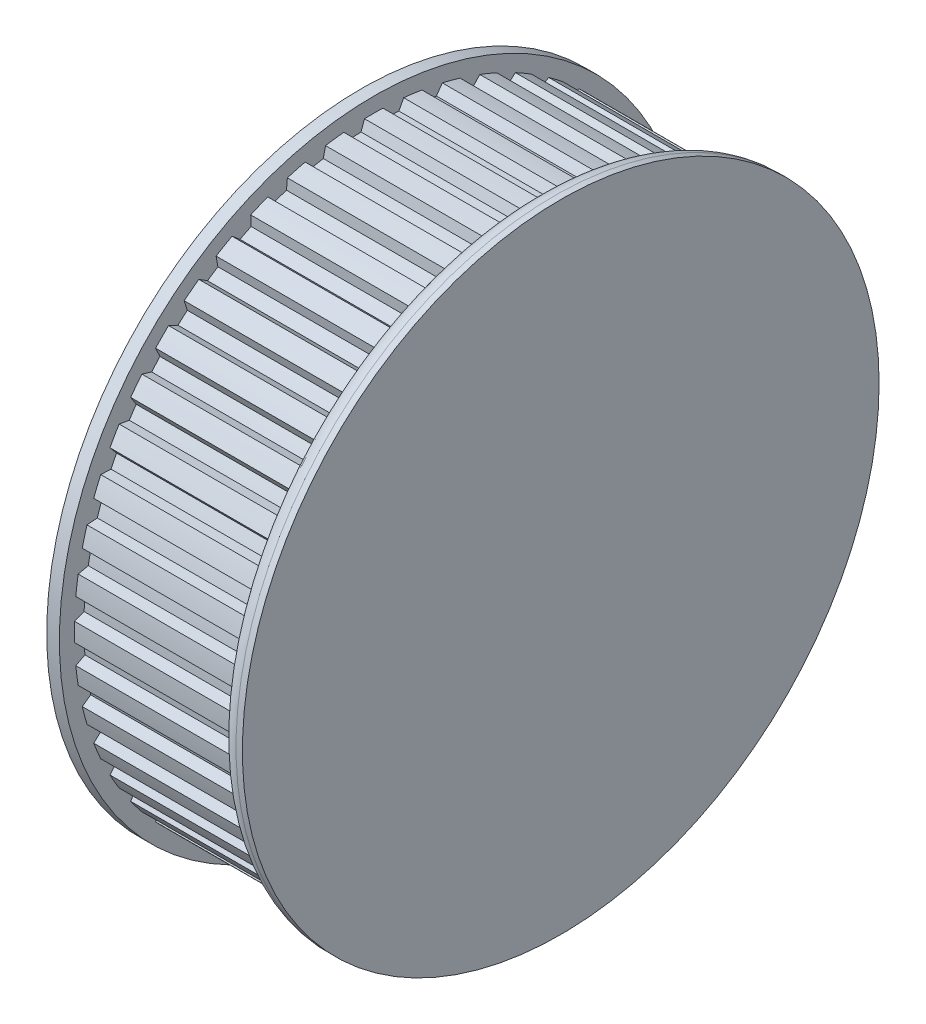
SolidWorks part; units mm, degrees
ref_plane "Front Plane" through (0, 0, 0) normal (0, 0, 1) x (1, 0, 0)
ref_plane "Top Plane" through (0, 0, 0) normal (0, 1, 0) x (1, 0, 0)
ref_plane "Right Plane" through (0, 0, 0) normal (1, 0, 0) x (0, 0, -1)
ref_plane "Plane1" through (0, 0, 0) normal (0, 0, -1) x (-1, 0, 0)
sketch "Sketch1" plane through (0, 0, 0) normal (0, 0, -1) x (-1, 0, 0)
  line L0 (-20.5, 37.625) -> (-20.5, 0)
  line L1 (-20.5, 0) -> (0, 0)
  line L2 (0, 0) -> (0, 37.625)
  line L3 (0, 37.625) -> (-20.5, 37.625)
  line L4 (-20.5, 0) -> (0, 0) construction
revolve "Revolve1" add sketch "Sketch1" angle 360 about L4
sketch "Sketch2" plane through (0, 0, 0) normal (-1, 0, 0) x (0, 0, 1)
  line L0 (-37.6072, 1.1569) -> (-36.3898, 1.6)
  line L1 (-36.2874, 3.1635) -> (-37.4365, 3.7617)
  arc A0 (-37.4365, 3.7617) -> (-37.6072, 1.1569) centre (0, 0) ccw
  arc A1 (-36.3898, 1.6) -> (-36.2874, 3.1635) centre (0, 0) cw
extrude "Cut-Extrude1" cut sketch "Sketch2" against normal through all
sketch "Sketch3" plane through (0, 0, 0) normal (-1, 0, 0) x (0, 0, 1)
  line L0 (-37.1345, 6.0557) -> (-35.8697, 6.3361)
  line L1 (-35.564, 7.8729) -> (-36.6252, 8.616)
  arc A0 (-36.6252, 8.616) -> (-37.1345, 6.0557) centre (0, 0) ccw
  arc A1 (-35.8697, 6.3361) -> (-35.564, 7.8729) centre (0, 0) cw
extrude "Cut-Extrude2" cut sketch "Sketch3" against normal through all
sketch "Sketch4" plane through (0, 0, 0) normal (-1, 0, 0) x (0, 0, 1)
  line L0 (-36.0263, 10.851) -> (-34.7358, 10.9639)
  line L1 (-34.2321, 12.4476) -> (-35.1873, 13.3228)
  arc A0 (-35.1873, 13.3228) -> (-36.0263, 10.851) centre (0, 0) ccw
  arc A1 (-34.7358, 10.9639) -> (-34.2321, 12.4476) centre (0, 0) cw
extrude "Cut-Extrude3" cut sketch "Sketch4" against normal through all
sketch "Sketch5" plane through (0, 0, 0) normal (-1, 0, 0) x (0, 0, 1)
  line L0 (-34.3018, 15.4605) -> (-33.0075, 15.404)
  line L1 (-32.3145, 16.8093) -> (-33.1473, 17.8017)
  arc A0 (-33.1473, 17.8017) -> (-34.3018, 15.4605) centre (0, 0) ccw
  arc A1 (-33.0075, 15.404) -> (-32.3145, 16.8093) centre (0, 0) cw
extrude "Cut-Extrude4" cut sketch "Sketch5" against normal through all
sketch "Sketch6" plane through (0, 0, 0) normal (-1, 0, 0) x (0, 0, 1)
  line L0 (-31.9903, 19.8055) -> (-30.7145, 19.5806)
  line L1 (-29.844, 20.8834) -> (-30.5401, 21.976)
  arc A0 (-30.5401, 21.976) -> (-31.9903, 19.8055) centre (0, 0) ccw
  arc A1 (-30.7145, 19.5806) -> (-29.844, 20.8834) centre (0, 0) cw
extrude "Cut-Extrude5" cut sketch "Sketch6" against normal through all
sketch "Sketch7" plane through (0, 0, 0) normal (-1, 0, 0) x (0, 0, 1)
  line L0 (-29.1315, 23.8117) -> (-27.896, 23.4221)
  line L1 (-26.8629, 24.6001) -> (-27.4104, 25.7743)
  arc A0 (-27.4104, 25.7743) -> (-29.1315, 23.8117) centre (0, 0) ccw
  arc A1 (-27.896, 23.4221) -> (-26.8629, 24.6001) centre (0, 0) cw
extrude "Cut-Extrude6" cut sketch "Sketch7" against normal through all
sketch "Sketch8" plane through (0, 0, 0) normal (-1, 0, 0) x (0, 0, 1)
  line L0 (-25.7743, 27.4104) -> (-24.6001, 26.8629)
  line L1 (-23.4221, 27.896) -> (-23.8117, 29.1315)
  arc A0 (-23.8117, 29.1315) -> (-25.7743, 27.4104) centre (0, 0) ccw
  arc A1 (-24.6001, 26.8629) -> (-23.4221, 27.896) centre (0, 0) cw
extrude "Cut-Extrude7" cut sketch "Sketch8" against normal through all
sketch "Sketch9" plane through (0, 0, 0) normal (-1, 0, 0) x (0, 0, 1)
  line L0 (-21.976, 30.5401) -> (-20.8834, 29.844)
  line L1 (-19.5806, 30.7145) -> (-19.8055, 31.9903)
  arc A0 (-19.8055, 31.9903) -> (-21.976, 30.5401) centre (0, 0) ccw
  arc A1 (-20.8834, 29.844) -> (-19.5806, 30.7145) centre (0, 0) cw
extrude "Cut-Extrude8" cut sketch "Sketch9" against normal through all
sketch "Sketch10" plane through (0, 0, 0) normal (-1, 0, 0) x (0, 0, 1)
  line L0 (-17.8017, 33.1473) -> (-16.8093, 32.3145)
  line L1 (-15.404, 33.0075) -> (-15.4605, 34.3018)
  arc A0 (-15.4605, 34.3018) -> (-17.8017, 33.1473) centre (0, 0) ccw
  arc A1 (-16.8093, 32.3145) -> (-15.404, 33.0075) centre (0, 0) cw
extrude "Cut-Extrude9" cut sketch "Sketch10" against normal through all
sketch "Sketch11" plane through (0, 0, 0) normal (-1, 0, 0) x (0, 0, 1)
  line L0 (-13.3228, 35.1873) -> (-12.4476, 34.2321)
  line L1 (-10.9639, 34.7358) -> (-10.851, 36.0263)
  arc A0 (-10.851, 36.0263) -> (-13.3228, 35.1873) centre (0, 0) ccw
  arc A1 (-12.4476, 34.2321) -> (-10.9639, 34.7358) centre (0, 0) cw
extrude "Cut-Extrude10" cut sketch "Sketch11" against normal through all
sketch "Sketch12" plane through (0, 0, 0) normal (-1, 0, 0) x (0, 0, 1)
  line L0 (-8.616, 36.6252) -> (-7.8729, 35.564)
  line L1 (-6.3361, 35.8697) -> (-6.0557, 37.1345)
  arc A0 (-6.0557, 37.1345) -> (-8.616, 36.6252) centre (0, 0) ccw
  arc A1 (-7.8729, 35.564) -> (-6.3361, 35.8697) centre (0, 0) cw
extrude "Cut-Extrude11" cut sketch "Sketch12" against normal through all
sketch "Sketch13" plane through (0, 0, 0) normal (-1, 0, 0) x (0, 0, 1)
  line L0 (-3.7617, 37.4365) -> (-3.1635, 36.2874)
  line L1 (-1.6, 36.3898) -> (-1.1569, 37.6072)
  arc A0 (-1.1569, 37.6072) -> (-3.7617, 37.4365) centre (0, 0) ccw
  arc A1 (-3.1635, 36.2874) -> (-1.6, 36.3898) centre (0, 0) cw
extrude "Cut-Extrude12" cut sketch "Sketch13" against normal through all
sketch "Sketch14" plane through (0, 0, 0) normal (-1, 0, 0) x (0, 0, 1)
  line L0 (1.1569, 37.6072) -> (1.6, 36.3898)
  line L1 (3.1635, 36.2874) -> (3.7617, 37.4365)
  arc A0 (3.7617, 37.4365) -> (1.1569, 37.6072) centre (0, 0) ccw
  arc A1 (1.6, 36.3898) -> (3.1635, 36.2874) centre (0, 0) cw
extrude "Cut-Extrude13" cut sketch "Sketch14" against normal through all
sketch "Sketch15" plane through (0, 0, 0) normal (-1, 0, 0) x (0, 0, 1)
  line L0 (6.0557, 37.1345) -> (6.3361, 35.8697)
  line L1 (7.8729, 35.564) -> (8.616, 36.6252)
  arc A0 (8.616, 36.6252) -> (6.0557, 37.1345) centre (0, 0) ccw
  arc A1 (6.3361, 35.8697) -> (7.8729, 35.564) centre (0, 0) cw
extrude "Cut-Extrude14" cut sketch "Sketch15" against normal through all
sketch "Sketch16" plane through (0, 0, 0) normal (-1, 0, 0) x (0, 0, 1)
  line L0 (10.851, 36.0263) -> (10.9639, 34.7358)
  line L1 (12.4476, 34.2321) -> (13.3228, 35.1873)
  arc A0 (13.3228, 35.1873) -> (10.851, 36.0263) centre (0, 0) ccw
  arc A1 (10.9639, 34.7358) -> (12.4476, 34.2321) centre (0, 0) cw
extrude "Cut-Extrude15" cut sketch "Sketch16" against normal through all
sketch "Sketch17" plane through (0, 0, 0) normal (-1, 0, 0) x (0, 0, 1)
  line L0 (15.4605, 34.3018) -> (15.404, 33.0075)
  line L1 (16.8093, 32.3145) -> (17.8017, 33.1473)
  arc A0 (17.8017, 33.1473) -> (15.4605, 34.3018) centre (0, 0) ccw
  arc A1 (15.404, 33.0075) -> (16.8093, 32.3145) centre (0, 0) cw
extrude "Cut-Extrude16" cut sketch "Sketch17" against normal through all
sketch "Sketch18" plane through (0, 0, 0) normal (-1, 0, 0) x (0, 0, 1)
  line L0 (19.8055, 31.9903) -> (19.5806, 30.7145)
  line L1 (20.8834, 29.844) -> (21.976, 30.5401)
  arc A0 (21.976, 30.5401) -> (19.8055, 31.9903) centre (0, 0) ccw
  arc A1 (19.5806, 30.7145) -> (20.8834, 29.844) centre (0, 0) cw
extrude "Cut-Extrude17" cut sketch "Sketch18" against normal through all
sketch "Sketch19" plane through (0, 0, 0) normal (-1, 0, 0) x (0, 0, 1)
  line L0 (23.8117, 29.1315) -> (23.4221, 27.896)
  line L1 (24.6001, 26.8629) -> (25.7743, 27.4104)
  arc A0 (25.7743, 27.4104) -> (23.8117, 29.1315) centre (0, 0) ccw
  arc A1 (23.4221, 27.896) -> (24.6001, 26.8629) centre (0, 0) cw
extrude "Cut-Extrude18" cut sketch "Sketch19" against normal through all
sketch "Sketch20" plane through (0, 0, 0) normal (-1, 0, 0) x (0, 0, 1)
  line L0 (27.4104, 25.7743) -> (26.8629, 24.6001)
  line L1 (27.896, 23.4221) -> (29.1315, 23.8117)
  arc A0 (29.1315, 23.8117) -> (27.4104, 25.7743) centre (0, 0) ccw
  arc A1 (26.8629, 24.6001) -> (27.896, 23.4221) centre (0, 0) cw
extrude "Cut-Extrude19" cut sketch "Sketch20" against normal through all
sketch "Sketch21" plane through (0, 0, 0) normal (-1, 0, 0) x (0, 0, 1)
  line L0 (30.5401, 21.976) -> (29.844, 20.8834)
  line L1 (30.7145, 19.5806) -> (31.9903, 19.8055)
  arc A0 (31.9903, 19.8055) -> (30.5401, 21.976) centre (0, 0) ccw
  arc A1 (29.844, 20.8834) -> (30.7145, 19.5806) centre (0, 0) cw
extrude "Cut-Extrude20" cut sketch "Sketch21" against normal through all
sketch "Sketch22" plane through (0, 0, 0) normal (-1, 0, 0) x (0, 0, 1)
  line L0 (33.1473, 17.8017) -> (32.3145, 16.8093)
  line L1 (33.0075, 15.404) -> (34.3018, 15.4605)
  arc A0 (34.3018, 15.4605) -> (33.1473, 17.8017) centre (0, 0) ccw
  arc A1 (32.3145, 16.8093) -> (33.0075, 15.404) centre (0, 0) cw
extrude "Cut-Extrude21" cut sketch "Sketch22" against normal through all
sketch "Sketch23" plane through (0, 0, 0) normal (-1, 0, 0) x (0, 0, 1)
  line L0 (35.1873, 13.3228) -> (34.2321, 12.4476)
  line L1 (34.7358, 10.9639) -> (36.0263, 10.851)
  arc A0 (36.0263, 10.851) -> (35.1873, 13.3228) centre (0, 0) ccw
  arc A1 (34.2321, 12.4476) -> (34.7358, 10.9639) centre (0, 0) cw
extrude "Cut-Extrude22" cut sketch "Sketch23" against normal through all
sketch "Sketch24" plane through (0, 0, 0) normal (-1, 0, 0) x (0, 0, 1)
  line L0 (36.6252, 8.616) -> (35.564, 7.8729)
  line L1 (35.8697, 6.3361) -> (37.1345, 6.0557)
  arc A0 (37.1345, 6.0557) -> (36.6252, 8.616) centre (0, 0) ccw
  arc A1 (35.564, 7.8729) -> (35.8697, 6.3361) centre (0, 0) cw
extrude "Cut-Extrude23" cut sketch "Sketch24" against normal through all
sketch "Sketch25" plane through (0, 0, 0) normal (-1, 0, 0) x (0, 0, 1)
  line L0 (37.4365, 3.7617) -> (36.2874, 3.1635)
  line L1 (36.3898, 1.6) -> (37.6072, 1.1569)
  arc A0 (37.6072, 1.1569) -> (37.4365, 3.7617) centre (0, 0) ccw
  arc A1 (36.2874, 3.1635) -> (36.3898, 1.6) centre (0, 0) cw
extrude "Cut-Extrude24" cut sketch "Sketch25" against normal through all
sketch "Sketch26" plane through (0, 0, 0) normal (-1, 0, 0) x (0, 0, 1)
  line L0 (37.6072, -1.1569) -> (36.3898, -1.6)
  line L1 (36.2874, -3.1635) -> (37.4365, -3.7617)
  arc A0 (37.4365, -3.7617) -> (37.6072, -1.1569) centre (0, 0) ccw
  arc A1 (36.3898, -1.6) -> (36.2874, -3.1635) centre (0, 0) cw
extrude "Cut-Extrude25" cut sketch "Sketch26" against normal through all
sketch "Sketch27" plane through (0, 0, 0) normal (-1, 0, 0) x (0, 0, 1)
  line L0 (37.1345, -6.0557) -> (35.8697, -6.3361)
  line L1 (35.564, -7.8729) -> (36.6252, -8.616)
  arc A0 (36.6252, -8.616) -> (37.1345, -6.0557) centre (0, 0) ccw
  arc A1 (35.8697, -6.3361) -> (35.564, -7.8729) centre (0, 0) cw
extrude "Cut-Extrude26" cut sketch "Sketch27" against normal through all
sketch "Sketch28" plane through (0, 0, 0) normal (-1, 0, 0) x (0, 0, 1)
  line L0 (36.0263, -10.851) -> (34.7358, -10.9639)
  line L1 (34.2321, -12.4476) -> (35.1873, -13.3228)
  arc A0 (35.1873, -13.3228) -> (36.0263, -10.851) centre (0, 0) ccw
  arc A1 (34.7358, -10.9639) -> (34.2321, -12.4476) centre (0, 0) cw
extrude "Cut-Extrude27" cut sketch "Sketch28" against normal through all
sketch "Sketch29" plane through (0, 0, 0) normal (-1, 0, 0) x (0, 0, 1)
  line L0 (34.3018, -15.4605) -> (33.0075, -15.404)
  line L1 (32.3145, -16.8093) -> (33.1473, -17.8017)
  arc A0 (33.1473, -17.8017) -> (34.3018, -15.4605) centre (0, 0) ccw
  arc A1 (33.0075, -15.404) -> (32.3145, -16.8093) centre (0, 0) cw
extrude "Cut-Extrude28" cut sketch "Sketch29" against normal through all
sketch "Sketch30" plane through (0, 0, 0) normal (-1, 0, 0) x (0, 0, 1)
  line L0 (31.9903, -19.8055) -> (30.7145, -19.5806)
  line L1 (29.844, -20.8834) -> (30.5401, -21.976)
  arc A0 (30.5401, -21.976) -> (31.9903, -19.8055) centre (0, 0) ccw
  arc A1 (30.7145, -19.5806) -> (29.844, -20.8834) centre (0, 0) cw
extrude "Cut-Extrude29" cut sketch "Sketch30" against normal through all
sketch "Sketch31" plane through (0, 0, 0) normal (-1, 0, 0) x (0, 0, 1)
  line L0 (29.1315, -23.8117) -> (27.896, -23.4221)
  line L1 (26.8629, -24.6001) -> (27.4104, -25.7743)
  arc A0 (27.4104, -25.7743) -> (29.1315, -23.8117) centre (0, 0) ccw
  arc A1 (27.896, -23.4221) -> (26.8629, -24.6001) centre (0, 0) cw
extrude "Cut-Extrude30" cut sketch "Sketch31" against normal through all
sketch "Sketch32" plane through (0, 0, 0) normal (-1, 0, 0) x (0, 0, 1)
  line L0 (25.7743, -27.4104) -> (24.6001, -26.8629)
  line L1 (23.4221, -27.896) -> (23.8117, -29.1315)
  arc A0 (23.8117, -29.1315) -> (25.7743, -27.4104) centre (0, 0) ccw
  arc A1 (24.6001, -26.8629) -> (23.4221, -27.896) centre (0, 0) cw
extrude "Cut-Extrude31" cut sketch "Sketch32" against normal through all
sketch "Sketch33" plane through (0, 0, 0) normal (-1, 0, 0) x (0, 0, 1)
  line L0 (21.976, -30.5401) -> (20.8834, -29.844)
  line L1 (19.5806, -30.7145) -> (19.8055, -31.9903)
  arc A0 (19.8055, -31.9903) -> (21.976, -30.5401) centre (0, 0) ccw
  arc A1 (20.8834, -29.844) -> (19.5806, -30.7145) centre (0, 0) cw
extrude "Cut-Extrude32" cut sketch "Sketch33" against normal through all
sketch "Sketch34" plane through (0, 0, 0) normal (-1, 0, 0) x (0, 0, 1)
  line L0 (17.8017, -33.1473) -> (16.8093, -32.3145)
  line L1 (15.404, -33.0075) -> (15.4605, -34.3018)
  arc A0 (15.4605, -34.3018) -> (17.8017, -33.1473) centre (0, 0) ccw
  arc A1 (16.8093, -32.3145) -> (15.404, -33.0075) centre (0, 0) cw
extrude "Cut-Extrude33" cut sketch "Sketch34" against normal through all
sketch "Sketch35" plane through (0, 0, 0) normal (-1, 0, 0) x (0, 0, 1)
  line L0 (13.3228, -35.1873) -> (12.4476, -34.2321)
  line L1 (10.9639, -34.7358) -> (10.851, -36.0263)
  arc A0 (10.851, -36.0263) -> (13.3228, -35.1873) centre (0, 0) ccw
  arc A1 (12.4476, -34.2321) -> (10.9639, -34.7358) centre (0, 0) cw
extrude "Cut-Extrude34" cut sketch "Sketch35" against normal through all
sketch "Sketch36" plane through (0, 0, 0) normal (-1, 0, 0) x (0, 0, 1)
  line L0 (8.616, -36.6252) -> (7.8729, -35.564)
  line L1 (6.3361, -35.8697) -> (6.0557, -37.1345)
  arc A0 (6.0557, -37.1345) -> (8.616, -36.6252) centre (0, 0) ccw
  arc A1 (7.8729, -35.564) -> (6.3361, -35.8697) centre (0, 0) cw
extrude "Cut-Extrude35" cut sketch "Sketch36" against normal through all
sketch "Sketch37" plane through (0, 0, 0) normal (-1, 0, 0) x (0, 0, 1)
  line L0 (3.7617, -37.4365) -> (3.1635, -36.2874)
  line L1 (1.6, -36.3898) -> (1.1569, -37.6072)
  arc A0 (1.1569, -37.6072) -> (3.7617, -37.4365) centre (0, 0) ccw
  arc A1 (3.1635, -36.2874) -> (1.6, -36.3898) centre (0, 0) cw
extrude "Cut-Extrude36" cut sketch "Sketch37" against normal through all
sketch "Sketch38" plane through (0, 0, 0) normal (-1, 0, 0) x (0, 0, 1)
  line L0 (-1.1569, -37.6072) -> (-1.6, -36.3898)
  line L1 (-3.1635, -36.2874) -> (-3.7617, -37.4365)
  arc A0 (-3.7617, -37.4365) -> (-1.1569, -37.6072) centre (0, 0) ccw
  arc A1 (-1.6, -36.3898) -> (-3.1635, -36.2874) centre (0, 0) cw
extrude "Cut-Extrude37" cut sketch "Sketch38" against normal through all
sketch "Sketch39" plane through (0, 0, 0) normal (-1, 0, 0) x (0, 0, 1)
  line L0 (-6.0557, -37.1345) -> (-6.3361, -35.8697)
  line L1 (-7.8729, -35.564) -> (-8.616, -36.6252)
  arc A0 (-8.616, -36.6252) -> (-6.0557, -37.1345) centre (0, 0) ccw
  arc A1 (-6.3361, -35.8697) -> (-7.8729, -35.564) centre (0, 0) cw
extrude "Cut-Extrude38" cut sketch "Sketch39" against normal through all
sketch "Sketch40" plane through (0, 0, 0) normal (-1, 0, 0) x (0, 0, 1)
  line L0 (-10.851, -36.0263) -> (-10.9639, -34.7358)
  line L1 (-12.4476, -34.2321) -> (-13.3228, -35.1873)
  arc A0 (-13.3228, -35.1873) -> (-10.851, -36.0263) centre (0, 0) ccw
  arc A1 (-10.9639, -34.7358) -> (-12.4476, -34.2321) centre (0, 0) cw
extrude "Cut-Extrude39" cut sketch "Sketch40" against normal through all
sketch "Sketch41" plane through (0, 0, 0) normal (-1, 0, 0) x (0, 0, 1)
  line L0 (-15.4605, -34.3018) -> (-15.404, -33.0075)
  line L1 (-16.8093, -32.3145) -> (-17.8017, -33.1473)
  arc A0 (-17.8017, -33.1473) -> (-15.4605, -34.3018) centre (0, 0) ccw
  arc A1 (-15.404, -33.0075) -> (-16.8093, -32.3145) centre (0, 0) cw
extrude "Cut-Extrude40" cut sketch "Sketch41" against normal through all
sketch "Sketch42" plane through (0, 0, 0) normal (-1, 0, 0) x (0, 0, 1)
  line L0 (-19.8055, -31.9903) -> (-19.5806, -30.7145)
  line L1 (-20.8834, -29.844) -> (-21.976, -30.5401)
  arc A0 (-21.976, -30.5401) -> (-19.8055, -31.9903) centre (0, 0) ccw
  arc A1 (-19.5806, -30.7145) -> (-20.8834, -29.844) centre (0, 0) cw
extrude "Cut-Extrude41" cut sketch "Sketch42" against normal through all
sketch "Sketch43" plane through (0, 0, 0) normal (-1, 0, 0) x (0, 0, 1)
  line L0 (-23.8117, -29.1315) -> (-23.4221, -27.896)
  line L1 (-24.6001, -26.8629) -> (-25.7743, -27.4104)
  arc A0 (-25.7743, -27.4104) -> (-23.8117, -29.1315) centre (0, 0) ccw
  arc A1 (-23.4221, -27.896) -> (-24.6001, -26.8629) centre (0, 0) cw
extrude "Cut-Extrude42" cut sketch "Sketch43" against normal through all
sketch "Sketch44" plane through (0, 0, 0) normal (-1, 0, 0) x (0, 0, 1)
  line L0 (-27.4104, -25.7743) -> (-26.8629, -24.6001)
  line L1 (-27.896, -23.4221) -> (-29.1315, -23.8117)
  arc A0 (-29.1315, -23.8117) -> (-27.4104, -25.7743) centre (0, 0) ccw
  arc A1 (-26.8629, -24.6001) -> (-27.896, -23.4221) centre (0, 0) cw
extrude "Cut-Extrude43" cut sketch "Sketch44" against normal through all
sketch "Sketch45" plane through (0, 0, 0) normal (-1, 0, 0) x (0, 0, 1)
  line L0 (-30.5401, -21.976) -> (-29.844, -20.8834)
  line L1 (-30.7145, -19.5806) -> (-31.9903, -19.8055)
  arc A0 (-31.9903, -19.8055) -> (-30.5401, -21.976) centre (0, 0) ccw
  arc A1 (-29.844, -20.8834) -> (-30.7145, -19.5806) centre (0, 0) cw
extrude "Cut-Extrude44" cut sketch "Sketch45" against normal through all
sketch "Sketch46" plane through (0, 0, 0) normal (-1, 0, 0) x (0, 0, 1)
  line L0 (-33.1473, -17.8017) -> (-32.3145, -16.8093)
  line L1 (-33.0075, -15.404) -> (-34.3018, -15.4605)
  arc A0 (-34.3018, -15.4605) -> (-33.1473, -17.8017) centre (0, 0) ccw
  arc A1 (-32.3145, -16.8093) -> (-33.0075, -15.404) centre (0, 0) cw
extrude "Cut-Extrude45" cut sketch "Sketch46" against normal through all
sketch "Sketch47" plane through (0, 0, 0) normal (-1, 0, 0) x (0, 0, 1)
  line L0 (-35.1873, -13.3228) -> (-34.2321, -12.4476)
  line L1 (-34.7358, -10.9639) -> (-36.0263, -10.851)
  arc A0 (-36.0263, -10.851) -> (-35.1873, -13.3228) centre (0, 0) ccw
  arc A1 (-34.2321, -12.4476) -> (-34.7358, -10.9639) centre (0, 0) cw
extrude "Cut-Extrude46" cut sketch "Sketch47" against normal through all
sketch "Sketch48" plane through (0, 0, 0) normal (-1, 0, 0) x (0, 0, 1)
  line L0 (-36.6252, -8.616) -> (-35.564, -7.8729)
  line L1 (-35.8697, -6.3361) -> (-37.1345, -6.0557)
  arc A0 (-37.1345, -6.0557) -> (-36.6252, -8.616) centre (0, 0) ccw
  arc A1 (-35.564, -7.8729) -> (-35.8697, -6.3361) centre (0, 0) cw
extrude "Cut-Extrude47" cut sketch "Sketch48" against normal through all
sketch "Sketch49" plane through (0, 0, 0) normal (-1, 0, 0) x (0, 0, 1)
  line L0 (-37.4365, -3.7617) -> (-36.2874, -3.1635)
  line L1 (-36.3898, -1.6) -> (-37.6072, -1.1569)
  arc A0 (-37.6072, -1.1569) -> (-37.4365, -3.7617) centre (0, 0) ccw
  arc A1 (-36.2874, -3.1635) -> (-36.3898, -1.6) centre (0, 0) cw
extrude "Cut-Extrude48" cut sketch "Sketch49" against normal through all
sketch "Sketch50" plane through (0, 0, 0) normal (0, 0, 1) x (1, 0, 0)
  line L0 (-1.5906, 39.5) -> (-1.5906, 0)
  line L1 (-1.5906, 0) -> (0.0026, 0)
  line L2 (0.0026, 0) -> (0.0026, 39.5)
  line L3 (0.0026, 39.5) -> (-1.5906, 39.5)
  line L4 (-1.5906, 0) -> (0.0026, 0) construction
revolve "Revolve2" add sketch "Sketch50" angle 360 about L4
hole_wizard "Ø2.0 (2) Diameter Hole1" positions "Sketch52" profile "Sketch51" hole size "Ø2.0" standard "ANSI Metric"
sketch "Sketch52" plane through (-1.5906, 0, 0) normal (-1, 0, 0) x (0, 0, 1)
  point P0 (0, 0)
sketch "Sketch51" plane through (-1.5906, 0, 0) normal (0, 1, 0) x (0, 0, 1)
  line L0 (0, 0) -> (0, 22.0906)
  line L1 (0, 22.0906) -> (1, 22.0906)
  line L2 (1, 22.0906) -> (1, 0)
  line L5 (1, 0) -> (0, 0)
  line L11 (0, -6.35) -> (0, 107.95) construction
  dimension "Thru Hole Dia." = 2
  dimension "Thru Hole Depth" = 22.0906
sketch "Sketch54" plane through (0, 0, 0) normal (1, 0, 0) x (0, 0, -1)
  line L0 (-3.7161, 6.4008) -> (-7.3705, 0)
  line L1 (-7.3705, 0) -> (-3.6748, -6.4008)
  line L2 (-3.6748, -6.4008) -> (3.5818, -6.4534)
  line L3 (3.5818, -6.4534) -> (7.4109, -0.1072)
  line L4 (7.4109, -0.1072) -> (3.7368, 6.4008)
  line L5 (3.7368, 6.4008) -> (-3.7161, 6.4008)
extrude "Cut-Extrude50" cut sketch "Sketch54" against normal through all both and the other way through all
sketch "Sketch58" plane through (20.5, 0, 0) normal (1, 0, 0) x (0, 0, -1)
  circle A0 centre (0, 0) radius 40
  point P2 (-31.0745, 14.1125)
  point P3 (-1.6281, 5.6786)
  point P4 (-34.6409, 1.5043)
extrude "Boss-Extrude2" add sketch "Sketch58" along normal blind 3 contours A0
fillet "Fillet3" radius 2.2 1 edges at (20.5, 0, -40)
